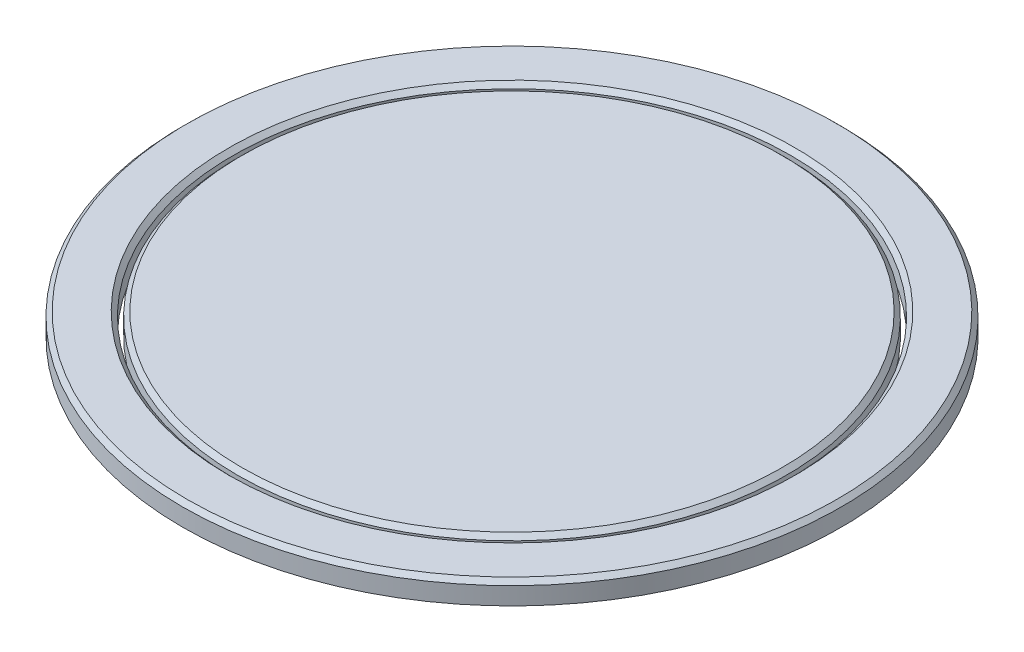
SolidWorks part; units mm, degrees
ref_plane "前视基准面" through (0, 0, 0) normal (0, 0, 1) x (1, 0, 0)
ref_plane "上视基准面" through (0, 0, 0) normal (0, 1, 0) x (1, 0, 0)
ref_plane "右视基准面" through (0, 0, 0) normal (1, 0, 0) x (0, 0, -1)
other "Configuration Table"
sketch "草图1" plane through (0, 0, 0) normal (0, 1, 0) x (1, 0, 0)
  circle A0 centre (0, 0) radius 25
  circle A1 centre (0, 0) radius 25.4
  circle A2 centre (0, 0) radius 30
  dimension "D1" = 50
  dimension "D2" = 50.8
  dimension "D3" = 60
extrude "凸台-拉伸1" add sketch "草图1" along normal blind 2 contours A2 A1 | A0
chamfer "倒角2" distance 0.4 angle 45 2 edges at (0, 2, 30) (0, 2, 25.4)
chamfer "倒角3" distance 0.4 angle 45 1 edges at (0, 2, 25)
